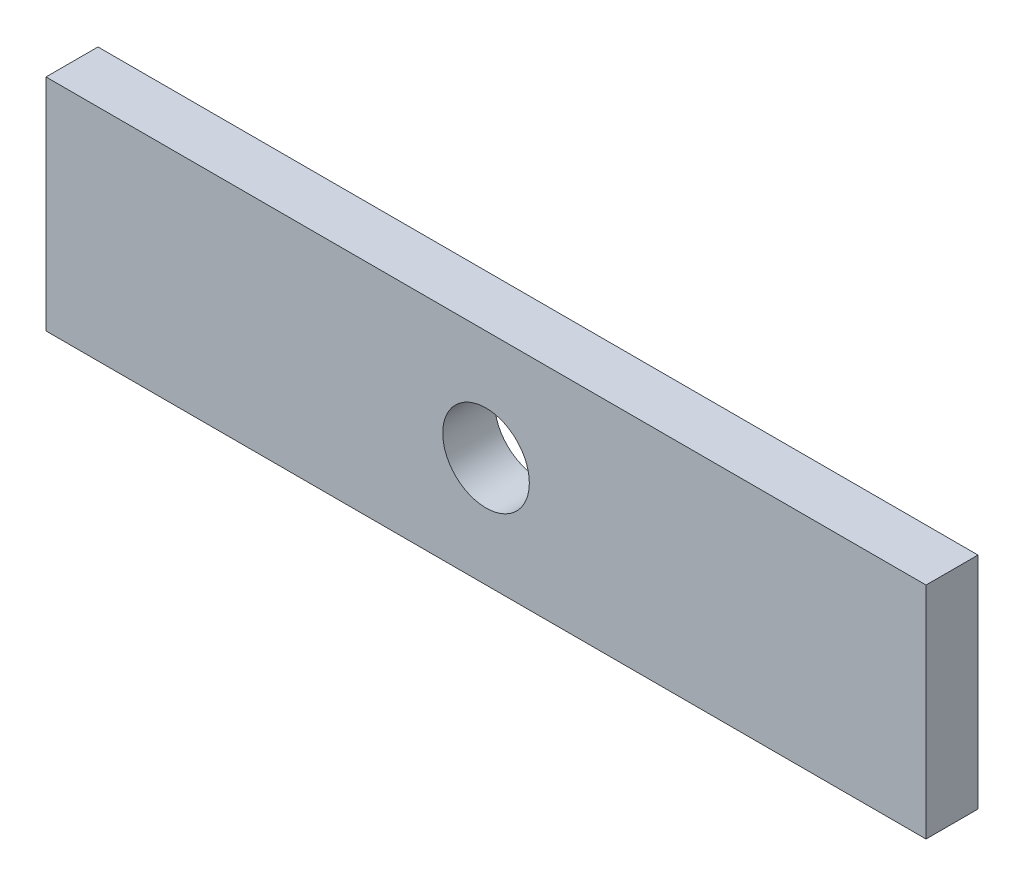
SolidWorks part; units mm, degrees
material "Plain Carbon Steel"
ref_plane "Front Plane" through (0, 0, 0) normal (0, 0, 1) x (1, 0, 0)
ref_plane "Top Plane" through (0, 0, 0) normal (0, 1, 0) x (1, 0, 0)
ref_plane "Right Plane" through (0, 0, 0) normal (1, 0, 0) x (0, 0, -1)
sketch "Sketch1" plane through (0, 0, 0) normal (0, 0, 1) x (1, 0, 0)
  line L1 (-25.4, 6.35) -> (25.4, 6.35)
  line L2 (-25.4, 6.35) -> (-25.4, -6.35)
  line L3 (-25.4, -6.35) -> (25.4, -6.35)
  line L4 (25.4, 6.35) -> (25.4, -6.35)
  line L5 (-25.4, 6.35) -> (25.4, -6.35) construction
  line L6 (-25.4, -6.35) -> (25.4, 6.35) construction
  circle A0 centre (0, 0) radius 2.5
  point P0 (0, 0)
  dimension "D3" = 5
  dimension "D1" = 50.8
  dimension "D2" = 12.7
  dimension "D4" = 6.35
  dimension "D5" = 25.4
extrude "Boss-Extrude1" add sketch "Sketch1" along normal blind 3
